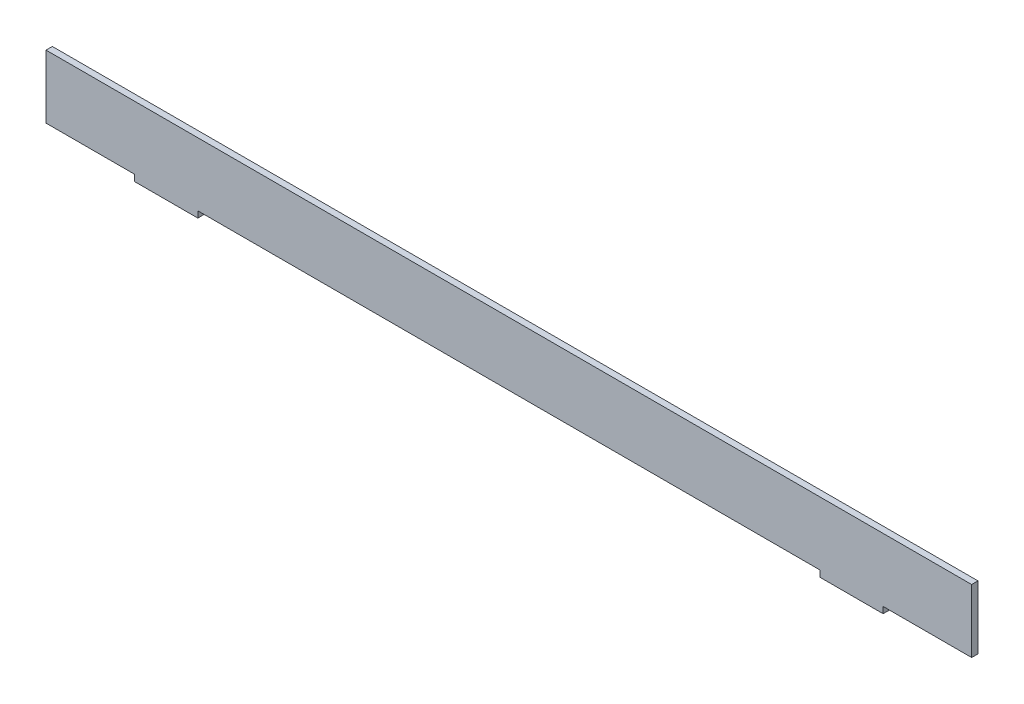
SolidWorks part; units mm, degrees
ref_plane "Alzado" through (0, 0, 0) normal (0, 0, 1) x (1, 0, 0)
ref_plane "Planta" through (0, 0, 0) normal (0, 1, 0) x (1, 0, 0)
ref_plane "Vista lateral" through (0, 0, 0) normal (1, 0, 0) x (0, 0, -1)
sketch "Croquis1" plane through (0, 0, 0) normal (0, 0, 1) x (1, 0, 0)
  line L0 (-177.5, -15) -> (-177.5, -18)
  line L1 (-219.5, -15) -> (-177.5, -15)
  line L2 (-219.5, -15) -> (-219.5, 15)
  line L3 (-219.5, 15) -> (219.5, 15)
  line L4 (219.5, -15) -> (219.5, 15)
  line L5 (-219.5, -15) -> (219.5, 15) construction
  line L6 (-219.5, 15) -> (219.5, -15) construction
  line L7 (-177.5, -18) -> (-147.5, -18)
  line L8 (-147.5, -18) -> (-147.5, -15)
  line L9 (-147.5, -15) -> (147.5, -15)
  line L10 (0, 15) -> (0, -33.9042) construction
  line L11 (147.5, -18) -> (147.5, -15)
  line L12 (177.5, -18) -> (147.5, -18)
  line L13 (177.5, -15) -> (177.5, -18)
  line L14 (177.5, -15) -> (219.5, -15)
  point P0 (0, 0)
  dimension "D1" = 439
  dimension "D2" = 30
  dimension "D3" = 30
  dimension "D4" = 3
  dimension "D5" = 42
extrude "Saliente-Extruir1" add sketch "Croquis1" along normal mid plane 3
